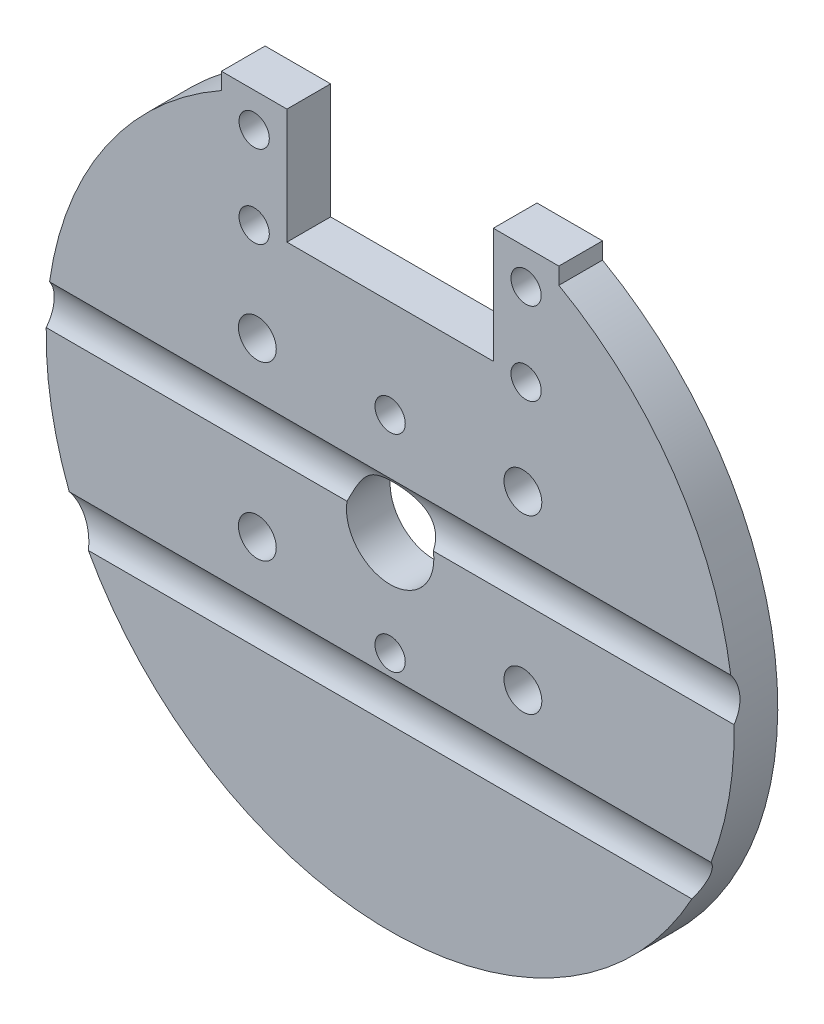
SolidWorks part; units mm, degrees
material "6061 Alloy"
ref_plane "Front Plane" through (0, 0, 0) normal (0, 0, 1) x (1, 0, 0)
ref_plane "Top Plane" through (0, 0, 0) normal (0, 1, 0) x (1, 0, 0)
ref_plane "Right Plane" through (0, 0, 0) normal (1, 0, 0) x (0, 0, -1)
sketch "Sketch1" plane through (0, 0, 0) normal (0, 0, 1) x (1, 0, 0)
  circle A0 centre (0, 0) radius 50
  dimension "D1" = 100
extrude "1/4" add sketch "Sketch1" along normal blind 6.35
sketch "Sketch2" plane through (0, 0, 6.35) normal (0, 0, 1) x (1, 0, 0)
  line L0 (0, 0) -> (0, 50) construction
  line L1 (-1.318, 74.311) -> (-1.318, 76.1424) construction
  line L3 (-15, 46) -> (-15, 29.25)
  line L4 (-15, 29.25) -> (15, 29.25)
  line L5 (15, 46) -> (15, 29.25)
  line L6 (0, 0) -> (0, 50) construction
  line L7 (-15, 37.625) -> (15, 37.625) construction
  line L8 (-30.7361, 76.1424) -> (28.1002, 76.1424)
  line L9 (-30.7361, 76.1424) -> (-30.7361, 46)
  line L10 (-30.7361, 46) -> (-15, 46)
  line L11 (28.1002, 76.1424) -> (28.1002, 46)
  line L12 (15, 46) -> (28.1002, 46)
  line L13 (-30.7361, 61.0712) -> (28.1002, 61.0712) construction
  circle A0 centre (0, 0) radius 50 construction
  point P6 (0, 37.625)
  point P130 (-1.318, 61.0712)
  dimension "D1" = 30
  dimension "D2" = 29.25
  dimension "D3" = 46
extrude "Cut-Extrude1" cut sketch "Sketch2" against normal up to surface (6.35 mm away) up to face at (50, 0, 0)
sketch "Sketch3" plane through (0, 0, 6.35) normal (0, 0, 1) x (1, 0, 0)
  line L1 (-15, 29.25) -> (-24.525, 29.25)
  line L2 (-15, 29.25) -> (-15, 46)
  line L3 (-15, 46) -> (-24.525, 46)
  line L4 (-24.525, 29.25) -> (-24.525, 46)
  line L5 (-19.7625, 46) -> (-19.7625, 29.25) construction
  line L6 (-15, 37.625) -> (-24.525, 37.625) construction
  line L7 (15, 29.25) -> (24.525, 29.25)
  line L8 (15, 29.25) -> (15, 46)
  line L9 (15, 46) -> (24.525, 46)
  line L10 (24.525, 29.25) -> (24.525, 46)
  line L11 (19.7625, 46) -> (19.7625, 29.25) construction
  line L12 (15, 37.625) -> (24.525, 37.625) construction
  point P168 (19.7625, 37.625)
  point P204 (-19.7625, 37.625)
  dimension "D1" = 9.525
  dimension "D2" = 9.525
  dimension "D3" = 46
extrude "Boss-Extrude2" add sketch "Sketch3" against normal up to surface (6.35 mm away) up to face at (0, 24.4167, 0)
sketch "Sketch4" plane through (0, 0, 6.35) normal (0, 0, 1) x (1, 0, 0)
  line L0 (-15, 35) -> (-24.525, 35) construction
  line L2 (-24.525, 46) -> (-24.525, 43.5721) construction
  line L3 (-19.7625, 41) -> (-19.7625, 35) construction
  line L4 (0, 0) -> (0, 50.3734) construction
  line L5 (-15, 46) -> (-15, 29.25) construction
  circle A0 centre (-19.7625, 41) radius 2.2
  circle A1 centre (-19.7625, 29) radius 2.2
  circle A2 centre (19.7625, 29) radius 2.2
  circle A3 centre (19.7625, 41) radius 2.2
  dimension "D1" = 4.4
  dimension "D2" = 6
  dimension "D3" = 35
extrude "M4_through" cut sketch "Sketch4" against normal up to surface (6.35 mm away) up to face at (0, 29.509, 0)
sketch "Sketch5" plane through (0, 0, 6.35) normal (0, 0, 1) x (1, 0, 0)
  circle A0 centre (0, 0) radius 6.35
  dimension "D1" = 12.7
extrude "Cut-Extrude2" cut sketch "Sketch5" against normal up to surface (6.35 mm away) up to face at (21.9625, 41, 0)
sketch "Sketch6" plane through (0, 0, 6.35) normal (0, 0, 1) x (1, 0, 0)
  circle A0 centre (0, 0) radius 15 construction
  circle A1 centre (0, 15) radius 2.2
  circle A2 centre (0, -15) radius 2.2
  point P13 (0, 0)
  dimension "D1" = 30
  dimension "D2" = 4.4
  dimension "D3" = 2
extrude "M4_through2" cut sketch "Sketch6" against normal up to surface (6.35 mm away) up to face at (6.35, 0, 0)
sketch "Sketch7" plane through (0, 0, 6.35) normal (0, 0, 1) x (1, 0, 0)
  line L0 (0, 0) -> (0, 38.8961) construction
  line L1 (-19.3, 15) -> (-19.3, -10) construction
  circle A0 centre (-19.3, 15) radius 2.75
  circle A1 centre (-19.3, -10) radius 2.75
  circle A2 centre (19.3, -10) radius 2.75
  circle A3 centre (19.3, 15) radius 2.75
  circle A4 centre (0, 0) radius 30 construction
  dimension "D2" = 5.5
  dimension "D3" = 25
  dimension "D4" = 60
  dimension "D1" = 19.3
  dimension "D5" = 15
extrude "M5_through" cut sketch "Sketch7" against normal up to surface (6.35 mm away) up to face at (2.2, 15, 0)
chamfer "Chamfer1" distance 2.5 angle 45 4 edges at (21.9625, 41, 0) (-17.5625, 29, 0) (-17.5625, 41, 0) (21.9625, 29, 0)
sketch "Sketch8" plane through (0, 0, 0) normal (1, 0, 0) x (0, 0, -1)
  line L0 (-10.35, 4) -> (-6.35, 4) construction
  line L2 (-6.35, 43.5721) -> (-6.35, -50) construction
  line L4 (-10.35, -21) -> (-6.35, -21) construction
  line L6 (-10.35, 4) -> (-10.35, -21) construction
  line L7 (-6.35, 17.75) -> (-6.35, 12.25) construction
  circle A0 centre (-10.35, 4) radius 5
  circle A1 centre (-10.35, -21) radius 5
  point P4 (-6.35, 15)
  dimension "D1" = 10
  dimension "D2" = 4
  dimension "D3" = 11
  dimension "D4" = 25
extrude "Cut-Extrude4" cut sketch "Sketch8" against normal through all and the other way through all
